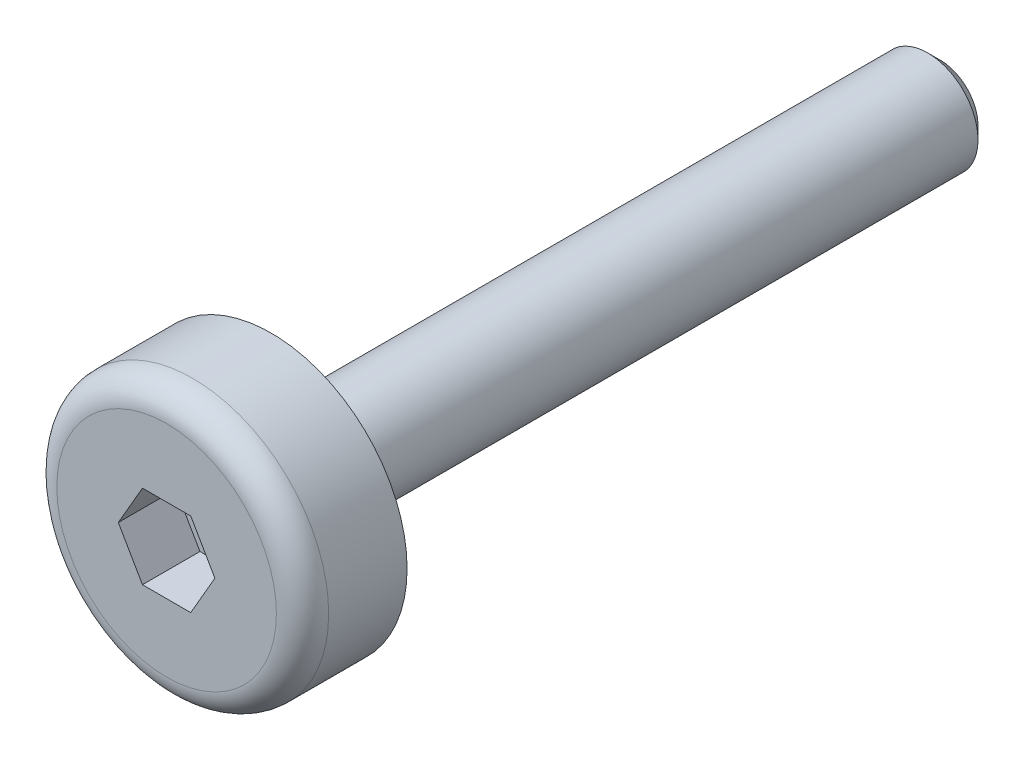
SolidWorks part; units mm, degrees
ref_plane "Front Plane" through (0, 0, 0) normal (0, 0, 1) x (1, 0, 0)
ref_plane "Top Plane" through (0, 0, 0) normal (0, 1, 0) x (1, 0, 0)
ref_plane "Right Plane" through (0, 0, 0) normal (1, 0, 0) x (0, 0, -1)
sketch "Screw Section" plane through (0, 0, 0) normal (0, 1, 0) x (1, 0, 0)
  line L0 (0, 16) -> (1.2, 16)
  line L1 (1.2, 16) -> (1.2, 0)
  line L2 (1.2, 0) -> (3.25, 0)
  line L3 (3.25, 0) -> (3.25, -2.5)
  line L4 (3.25, -2.5) -> (0, -2.5)
  line L5 (0, -2.5) -> (0, 16)
  line L6 (0, -10.123) -> (0, 10.123) construction
  dimension "D1" = 1.2
  dimension "D2" = 3.25
  dimension "D3" = 16
  dimension "D4" = 2.5
  dimension "D5" = 10.123
  dimension "D6" = 10.123
revolve "Screw Blank Revolve" add sketch "Screw Section" angle 360 about L6
chamfer "Shank Tip Chamfer" distance 0.3 1 edges at (1.2, 0, -16)
fillet "Pan Head Round" radius 0.625 1 edges at (3.25, 0, 2.5)
ref_plane "Head Crown Plane" through (0, 0, 2.5) normal (0, 0, 1) x (1, 0, 0)
sketch "Hex Drive Sketch" plane through (0, 0, 2.5) normal (0, 0, 1) x (1, 0, 0)
  line L1 (1.1547, 0) -> (0.5774, 1)
  line L2 (0.5774, 1) -> (-0.5774, 1)
  line L3 (-0.5774, 1) -> (-1.1547, 0)
  line L4 (-1.1547, 0) -> (-0.5774, -1)
  line L5 (-0.5774, -1) -> (0.5774, -1)
  line L6 (0.5774, -1) -> (1.1547, 0)
  circle A0 centre (0, 0) radius 1 construction
  dimension "D1" = 2
extrude "Hex Drive Cut" cut sketch "Hex Drive Sketch" against normal blind 1.375
equation "\"nominal_length\"= 16.0mm 'Screw length: under pan head or including flat head"
equation "\"model_shank_radius\"= 1.2mm 'Clearance envelope minor shank radius; thread is not modeled"
equation "\"head_diameter\"= 6.5mm 'Head outside diameter"
equation "\"head_height\"= 2.5mm 'Head axial height"
equation "\"drive_across_flats\"= 2mm 'Hex drive across flats"
equation "\"tip_chamfer\"= 0.3mm 'Shank tip chamfer"
equation "\"head_round\"= 0.625mm 'Pan head crown edge radius"
equation "\"drive_depth\"= 1.375mm 'Hex socket depth"
equation "\"axis_reference_halfspan\"= 10.123mm 'Half display length of the construction axis; avoids sharing a profile endpoint"
equation "\"D1@Screw Section\"= \"model_shank_radius\""
equation "\"D2@Screw Section\"= \"head_diameter\" / 2"
equation "\"D3@Screw Section\"= \"nominal_length\""
equation "\"D4@Screw Section\"= \"head_height\""
equation "\"D5@Screw Section\"= \"axis_reference_halfspan\""
equation "\"D6@Screw Section\"= \"axis_reference_halfspan\""
equation "\"full_turn\"= 360deg 'Full circular extent for revolves and patterns"
equation "\"D1@Screw Blank Revolve\"= \"full_turn\""
equation "\"D1@Shank Tip Chamfer\"= \"tip_chamfer\""
equation "\"D1@Pan Head Round\"= \"head_round\""
equation "\"D1@Head Crown Plane\"= \"head_height\""
equation "\"D1@Hex Drive Sketch\"= \"drive_across_flats\""
equation "\"D1@Hex Drive Cut\"= \"drive_depth\""
